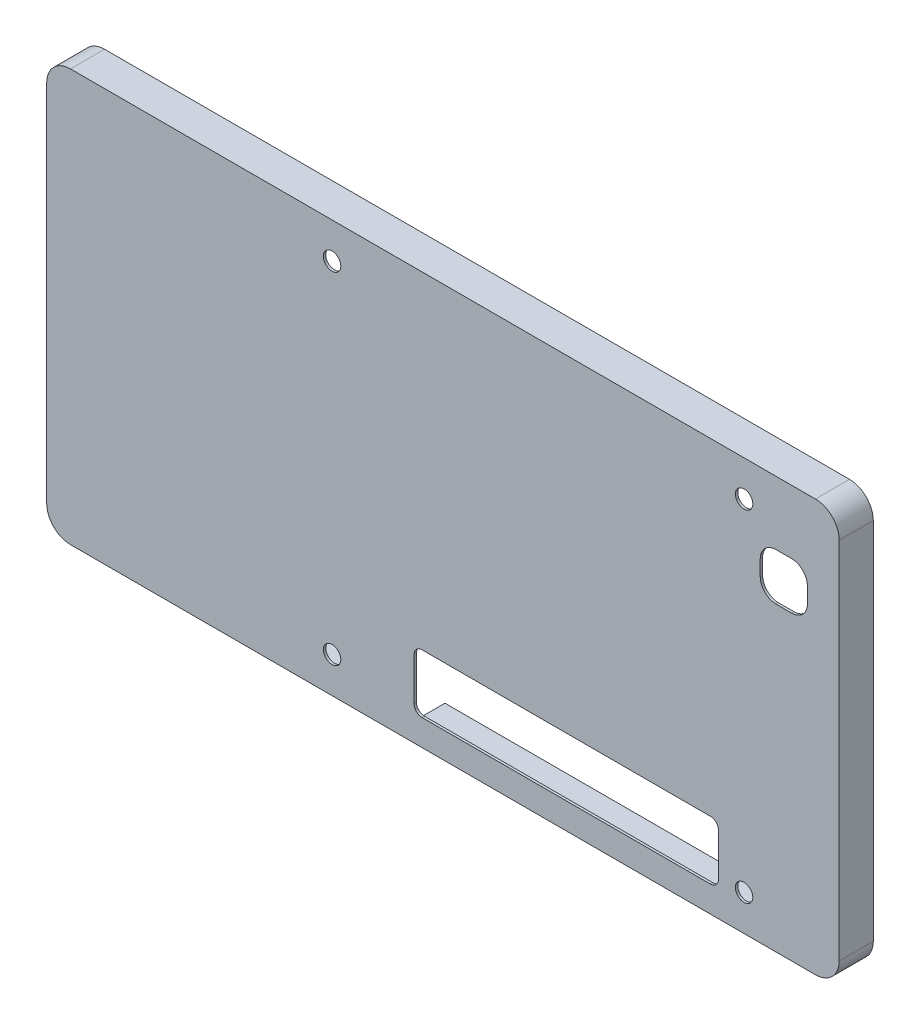
SolidWorks part; units mm, degrees
ref_plane "Front Plane" through (0, 0, 0) normal (0, 0, 1) x (1, 0, 0)
ref_plane "Top Plane" through (0, 0, 0) normal (0, 1, 0) x (1, 0, 0)
ref_plane "Right Plane" through (0, 0, 0) normal (1, 0, 0) x (0, 0, -1)
other "Configuration Table"
sketch "草图1" plane through (0, 0, 1046.4833) normal (0, 0, 1) x (1, 0, 0)
  line L0 (887.3759, 1046.1318) -> (981.3761, 1046.1318) construction
  line L1 (884.3886, 1046.1318) -> (984.3634, 1046.1318)
  line L2 (884.3886, 1046.1318) -> (884.3886, 994.1571)
  line L3 (884.3886, 994.1571) -> (984.3634, 994.1571)
  line L4 (984.3634, 1046.1318) -> (984.3634, 994.1571)
  line L6 (884.3886, 997.1444) -> (884.3886, 1043.1445) construction
  line L7 (984.3634, 1043.1445) -> (984.3634, 997.1444) construction
  line L8 (981.3761, 994.1571) -> (887.3759, 994.1571) construction
extrude "凸台-拉伸1" add sketch "草图1" along normal blind 8.6
sketch "草图2" plane through (0, 0, 1046.4833) normal (0, 0, -1) x (-1, 0, 0)
  line L0 (-884.3886, 1046.1318) -> (-884.3886, 994.1571) construction
  line L1 (-982.3634, 1044.1318) -> (-886.3886, 1044.1318)
  line L2 (-982.3634, 1044.1318) -> (-982.3634, 996.1571)
  line L3 (-982.3634, 996.1571) -> (-886.3886, 996.1571)
  line L4 (-886.3886, 1044.1318) -> (-886.3886, 996.1571)
  line L5 (-984.3634, 1046.1318) -> (-884.3886, 1046.1318) construction
  line L6 (-884.3886, 994.1571) -> (-984.3634, 994.1571) construction
  line L7 (-984.3634, 994.1571) -> (-984.3634, 1046.1318) construction
  dimension "D1" = 2
  dimension "D2" = 2
  dimension "D3" = 2
  dimension "D4" = 2
extrude "切除-拉伸1" cut sketch "草图2" against normal blind 4
sketch "草图3" plane through (0, 0, 1046.4833) normal (0, 0, -1) x (-1, 0, 0)
  line L0 (-886.3886, 996.1571) -> (-886.3886, 1044.1318) construction
  line L1 (-886.3886, 1039.1318) -> (-884.3886, 1039.1318)
  line L2 (-886.3886, 1039.1318) -> (-886.3886, 1029.1318)
  line L3 (-886.3886, 1029.1318) -> (-884.3886, 1029.1318)
  line L4 (-884.3886, 1039.1318) -> (-884.3886, 1029.1318)
  line L5 (-884.3886, 1046.1318) -> (-884.3886, 994.1571) construction
  line L8 (-984.3634, 1046.1318) -> (-884.3886, 1046.1318) construction
  line L9 (-886.3886, 1025.1318) -> (-884.3886, 1025.1318)
  line L10 (-886.3886, 1025.1318) -> (-886.3886, 1015.1571)
  line L11 (-886.3886, 1015.1571) -> (-884.3886, 1015.1571)
  line L12 (-884.3886, 1025.1318) -> (-884.3886, 1015.1571)
  line L13 (-886.3886, 1011.1571) -> (-884.3886, 1011.1571)
  line L14 (-886.3886, 1011.1571) -> (-886.3886, 1001.1571)
  line L15 (-886.3886, 1001.1571) -> (-884.3886, 1001.1571)
  line L16 (-884.3886, 1011.1571) -> (-884.3886, 1001.1571)
  line L17 (-884.3886, 994.1571) -> (-984.3634, 994.1571) construction
  dimension "D1" = 7
  dimension "D2" = 7
  dimension "D3" = 17
  dimension "D4" = 17
  dimension "D5" = 21
  dimension "D6" = 21
extrude "切除-拉伸2" cut sketch "草图3" against normal blind 3.35
sketch "草图4" plane through (0, 0, 1050.4833) normal (0, 0, -1) x (-1, 0, 0)
  line L0 (-984.3634, 1046.1318) -> (-884.3886, 1046.1318) construction
  line L1 (-969.1301, 1004.8444) -> (-930.7375, 1004.8444)
  line L2 (-969.1301, 1004.8444) -> (-969.1301, 997.4444)
  line L3 (-969.1301, 997.4444) -> (-930.7375, 997.4444)
  line L4 (-930.7375, 1004.8444) -> (-930.7375, 997.4444)
  line L5 (-980.351, 1038.1195) -> (-974.401, 1038.1195)
  line L6 (-980.351, 1038.1195) -> (-980.351, 1032.1695)
  line L7 (-980.351, 1032.1695) -> (-974.401, 1032.1695)
  line L8 (-974.401, 1038.1195) -> (-974.401, 1032.1695)
  line L9 (-984.3634, 994.1571) -> (-984.3634, 1046.1318) construction
  line L10 (-884.3886, 1046.1318) -> (-884.3886, 1039.1318) construction
  line L11 (-884.3886, 1001.1571) -> (-884.3886, 994.1571) construction
  line L12 (-884.3886, 994.1571) -> (-984.3634, 994.1571) construction
  circle A0 centre (-920.3886, 1041.6318) radius 1.1
  circle A1 centre (-920.3886, 998.6571) radius 1.1
  circle A2 centre (-972.3634, 998.6571) radius 1.1
  circle A3 centre (-972.3634, 1041.6318) radius 1.1
  dimension "D1" = 4.5
  dimension "D2" = 12
  dimension "D3" = 4.5
  dimension "D4" = 36
  dimension "D5" = 36
  dimension "D6" = 4.5
  dimension "D7" = 4.5
  dimension "D8" = 12
extrude "切除-拉伸3" cut sketch "草图4" against normal through all
sketch "草图6" plane through (0, 0, 1046.4833) normal (0, 0, -1) x (-1, 0, 0)
  line L1 (-930.3263, 1000.9528) -> (-923.5663, 1000.9528)
  line L2 (-930.3263, 1000.9528) -> (-930.3263, 994.1571)
  line L3 (-930.3263, 994.1571) -> (-923.5663, 994.1571)
  line L4 (-923.5663, 1000.9528) -> (-923.5663, 994.1571)
  line L5 (-884.3886, 994.1571) -> (-984.3634, 994.1571) construction
  line L6 (-929.8263, 995.0827) -> (-929.8263, 1000.0827) construction
  line L7 (-924.0663, 995.0827) -> (-924.0663, 1000.0827) construction
  dimension "D1" = 0.5
  dimension "D2" = 0.5
sketch "草图7" plane through (0, 0, 1055.0833) normal (0, 0, 1) x (1, 0, 0)
  line L0 (984.3634, 994.1571) -> (984.3634, 1046.1318) construction
  line L5 (984.3634, 1046.1318) -> (884.3886, 1046.1318) construction
  line L11 (885.8886, 1019.8318) -> (982.8634, 1019.8318)
  line L13 (982.8634, 1008.1318) -> (927.7634, 1008.1318)
  line L30 (934.1634, 1044.6318) -> (934.1634, 1033.1318)
  line L31 (934.1634, 1033.1318) -> (935.6634, 1033.1318)
  line L32 (935.6634, 1044.6318) -> (935.6634, 1033.1318)
  line L36 (927.7634, 1008.1318) -> (927.7634, 1006.6318)
  line L42 (927.7634, 1006.6318) -> (927.7634, 995.6571)
  line L44 (929.2634, 1006.6318) -> (929.2634, 995.6571)
  line L45 (929.2634, 1006.6318) -> (982.8634, 1006.6318)
  line L46 (961.9634, 1021.3318) -> (961.9634, 1031.2318)
  line L47 (961.9634, 1031.2318) -> (943.9634, 1031.2318)
  line L48 (943.9634, 1031.2318) -> (943.9634, 1032.7318)
  line L49 (943.9634, 1032.7318) -> (963.4634, 1032.7318)
  line L50 (963.4634, 1032.7318) -> (963.4634, 1021.3318)
  line L51 (982.8634, 1021.3318) -> (963.4634, 1021.3318)
  line L53 (926.0634, 1021.3318) -> (926.0634, 1031.3118)
  line L56 (902.8634, 1031.3118) -> (902.8634, 1044.6318)
  line L58 (904.3634, 1044.6318) -> (904.3634, 1032.8118)
  line L59 (904.3634, 1032.8118) -> (927.5634, 1032.8118)
  line L60 (927.5634, 1032.8118) -> (927.5634, 1021.3318)
  line L61 (961.9634, 1021.3318) -> (927.5634, 1021.3318)
  line L62 (926.0634, 1021.3318) -> (885.8886, 1021.3318)
  line L64 (926.0634, 1031.3118) -> (902.8634, 1031.3118)
  line L65 (982.8634, 1021.3318) -> (982.8634, 1044.6318)
  line L66 (982.8634, 1044.6318) -> (935.6634, 1044.6318)
  line L67 (904.3634, 1044.6318) -> (934.1634, 1044.6318)
  line L68 (885.8886, 1044.6318) -> (885.8886, 1021.3318)
  line L70 (902.8634, 1044.6318) -> (885.8886, 1044.6318)
  line L71 (982.8634, 1008.1318) -> (982.8634, 1019.8318)
  line L72 (885.8886, 1019.8318) -> (885.8886, 995.6571)
  line L73 (885.8886, 995.6571) -> (927.7634, 995.6571)
  line L74 (929.2634, 995.6571) -> (982.8634, 995.6571)
  line L75 (982.8634, 1006.6318) -> (982.8634, 995.6571)
  dimension "D2" = 1.5
  dimension "D3" = 20.9
  dimension "D4" = 13.4
  dimension "D5" = 1.5
  dimension "D6" = 1.5
  dimension "D7" = 38
  dimension "D8" = 56.6
  dimension "D11" = 1.5
  dimension "D12" = 19.5
  dimension "D14" = 56.8
  dimension "D15" = 26.3
  dimension "D16" = 48.7
  dimension "D17" = 13
  dimension "D18" = 1.5
  dimension "D19" = 1.5
  dimension "D20" = 1.5
  dimension "D22" = 14.82
  dimension "D23" = 1.5
  dimension "D24" = 81.5
  dimension "D25" = 1.5
fillet "圆角1" radius 3 4 edges at (984.3634, 1046.1318, 1050.7833) (884.3886, 1046.1318, 1050.7833) (884.3886, 994.1571, 1050.7833) (984.3634, 994.1571, 1050.7833)
fillet "圆角3" radius 2 4 edges at (974.401, 1038.1195, 1052.7833) (974.401, 1032.1695, 1052.7833) (980.351, 1032.1695, 1052.7833) (980.351, 1038.1195, 1052.7833)
sketch "草图12" plane through (0, 0, 1050.4833) normal (0, 0, -1) x (-1, 0, 0)
  line L1 (-959.8699, 1027.3424) -> (-950.8699, 1027.3424)
  line L2 (-959.8699, 1027.3424) -> (-959.8699, 1018.3424)
  line L3 (-959.8699, 1018.3424) -> (-950.8699, 1018.3424)
  line L4 (-950.8699, 1027.3424) -> (-950.8699, 1018.3424)
sketch "草图13" plane through (0, 0, 1050.4833) normal (0, 0, -1) x (-1, 0, 0)
  line L1 (-944.4751, 1027.3019) -> (-927.483, 1027.3019)
  line L2 (-944.4751, 1027.3019) -> (-944.4751, 1010.2546)
  line L3 (-944.4751, 1010.2546) -> (-927.483, 1010.2546)
  line L4 (-927.483, 1027.3019) -> (-927.483, 1010.2546)
extrude "切除-拉伸14" cut sketch "草图7" against normal blind 4
fillet "圆角7" radius 2 32 edges at (885.8886, 995.6571, 1053.0833) (982.8634, 995.6571, 1053.0833) (927.7634, 995.6571, 1053.0833) (927.7634, 1008.1318, 1053.0833) (982.8634, 1008.1318, 1053.0833) (982.8634, 1006.6318, 1053.0833) (982.8634, 1019.8318, 1053.0833) (885.8886, 1019.8318, 1053.0833) (982.8634, 1021.3318, 1053.0833) (982.8634, 1044.6318, 1053.0833) (963.4634, 1021.3318, 1053.0833) (963.4634, 1032.7318, 1053.0833) (961.9634, 1031.2318, 1053.0833) (961.9634, 1021.3318, 1053.0833) (927.5634, 1021.3318, 1053.0833) (935.6634, 1044.6318, 1053.0833) (904.3634, 1044.6318, 1053.0833) (904.3634, 1032.8118, 1053.0833) (927.5634, 1032.8118, 1053.0833) (885.8886, 1021.3318, 1053.0833) (926.0634, 1021.3318, 1053.0833) (934.1634, 1044.6318, 1053.0833) (926.0634, 1031.3118, 1053.0833) (902.8634, 1031.3118, 1053.0833) (902.8634, 1044.6318, 1053.0833) (885.8886, 1044.6318, 1053.0833) (886.3886, 996.1571, 1048.4833) (886.3886, 1044.1318, 1048.4833) (982.3634, 996.1571, 1048.4833) (982.3634, 1044.1318, 1048.4833) (929.2634, 995.6571, 1053.0833) (929.2634, 1006.6318, 1053.0833)
fillet "圆角8" radius 1 4 edges at (930.7375, 997.4444, 1050.7833) (930.7375, 1004.8444, 1050.7833) (969.1301, 997.4444, 1050.7833) (969.1301, 1004.8444, 1050.7833)
sketch "草图14" plane through (0, 0, 1055.0833) normal (0, 0, 1) x (1, 0, 0)
  line L1 (982.0396, 1016.6318) -> (984.3634, 1016.6318)
  line L2 (982.0396, 1016.6318) -> (982.0396, 1009.8318)
  line L3 (982.0396, 1009.8318) -> (984.3634, 1009.8318)
  line L4 (984.3634, 1016.6318) -> (984.3634, 1009.8318)
  line L5 (981.3634, 1046.1318) -> (887.3886, 1046.1318) construction
  line L7 (984.3634, 997.1571) -> (984.3634, 1043.1318) construction
  dimension "D1" = 29.5
  dimension "D2" = 36.3
extrude "切除-拉伸15" cut sketch "草图14" against normal blind 2
sketch "草图15" plane through (984.3634, 0, 0) normal (1, 0, 0) x (0, 0, -1)
  line L1 (-1055.0833, 1046.1318) -> (-1050.7833, 1046.1318)
  line L2 (-1055.0833, 1046.1318) -> (-1055.0833, 994.1571)
  line L3 (-1055.0833, 994.1571) -> (-1050.7833, 994.1571)
  line L4 (-1050.7833, 1046.1318) -> (-1050.7833, 994.1571)
  line L5 (-1055.0833, 1046.1318) -> (-1046.4833, 1046.1318) construction
  line L7 (-1055.0833, 1016.6318) -> (-1055.0833, 1043.1318) construction
  dimension "D1" = 4.3
extrude "切除-拉伸16" cut sketch "草图15" against normal through all
extrude "切除-拉伸17" cut sketch "草图6" against normal blind 4
